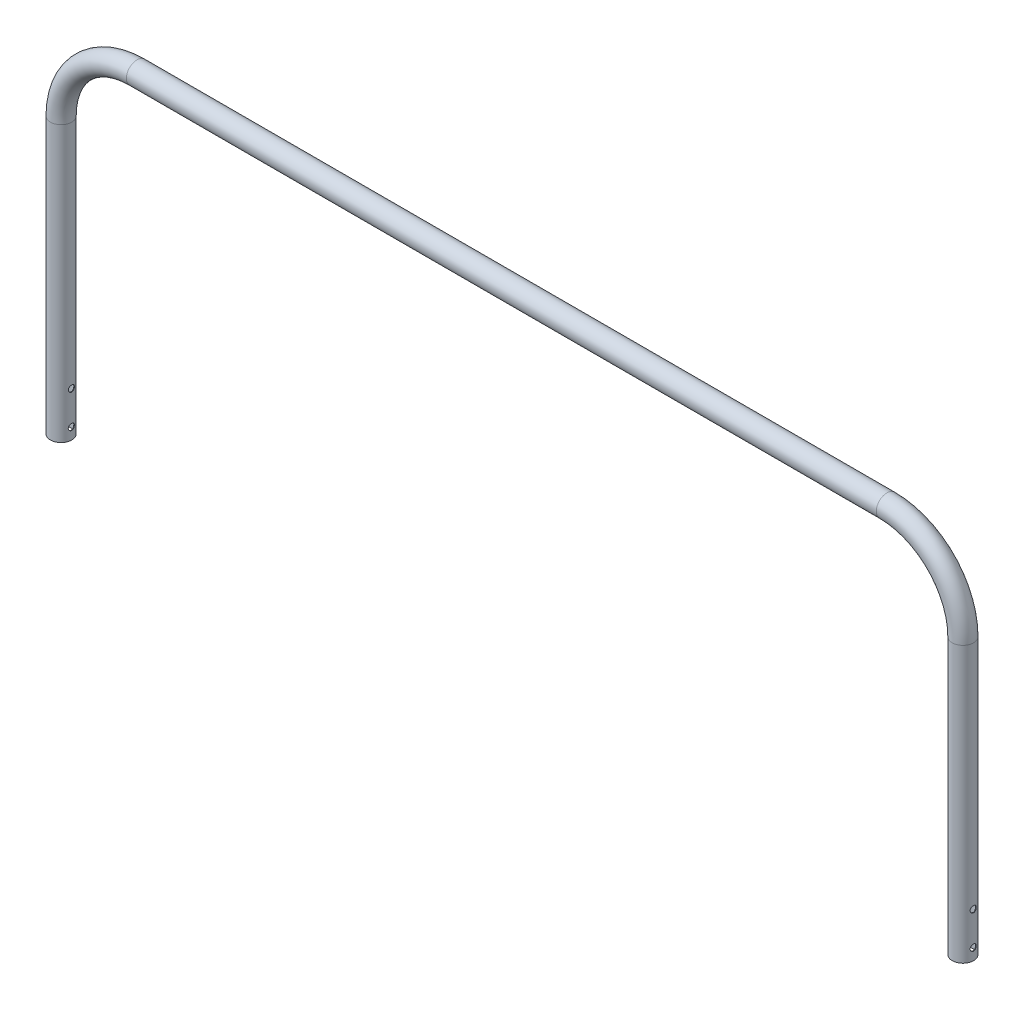
SolidWorks part; units mm, degrees
ref_plane "Front Plane" through (0, 0, 0) normal (0, 0, 1) x (1, 0, 0)
ref_plane "Top Plane" through (0, 0, 0) normal (0, 1, 0) x (1, 0, 0)
ref_plane "Right Plane" through (0, 0, 0) normal (1, 0, 0) x (0, 0, -1)
sketch "Sketch1" plane through (0, 0, 0) normal (0, 0, 1) x (1, 0, 0)
  line L0 (0, 0) -> (0, 290)
  line L1 (80, 370) -> (870, 370)
  line L2 (950, 290) -> (950, 0)
  arc A0 (950, 290) -> (870, 370) centre (870, 290) ccw
  arc A1 (80, 370) -> (0, 290) centre (80, 290) ccw
  point P7 (950, 370)
  point P10 (0, 370)
  dimension "D3" = 80
  dimension "D1" = 370
  dimension "D2" = 950
sketch "Sketch2" plane through (0, 0, 0) normal (0, 1, 0) x (1, 0, 0)
  circle A0 centre (0, 0) radius 11.25
  circle A1 centre (0, 0) radius 10.65
  dimension "D1" = 22.5
  dimension "D2" = 0.6
sweep "Sweep1" add profiles "Sketch2" path "Sketch1"
sketch "Sketch3" plane through (0, 0, 0) normal (1, 0, 0) x (0, 0, -1)
  line L0 (0, 0) -> (0, 264.335) construction
  line L1 (-11.25, 0) -> (11.25, 0) construction
  circle A0 centre (0, 12) radius 3.2382
  circle A1 centre (0, 47) radius 3.2382
  dimension "D1" = 12
  dimension "D2" = 35
extrude "Cut-Extrude1" cut sketch "Sketch3" against normal through all both and the other way through all
